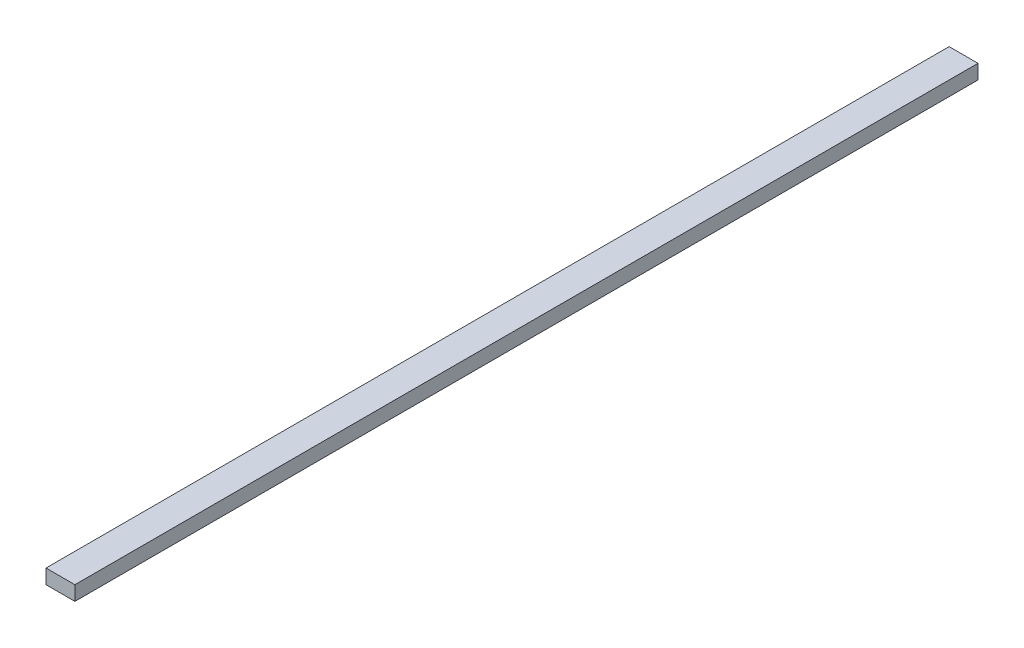
SolidWorks part; units mm, degrees
ref_plane "Front Plane" through (0, 0, 0) normal (0, 0, 1) x (1, 0, 0)
ref_plane "Top Plane" through (0, 0, 0) normal (0, 1, 0) x (1, 0, 0)
ref_plane "Right Plane" through (0, 0, 0) normal (1, 0, 0) x (0, 0, -1)
sketch "Sketch1" plane through (0, 0, 0) normal (0, 0, 1) x (1, 0, 0)
  line L1 (-20, 10) -> (20, 10)
  line L2 (-20, 10) -> (-20, -10)
  line L3 (-20, -10) -> (20, -10)
  line L4 (20, 10) -> (20, -10)
  line L5 (-20, 10) -> (20, -10) construction
  line L6 (-20, -10) -> (20, 10) construction
  point P0 (0, 0)
  dimension "D1" = 40
  dimension "D2" = 20
extrude "Boss-Extrude1" add sketch "Sketch1" along normal blind 1250
